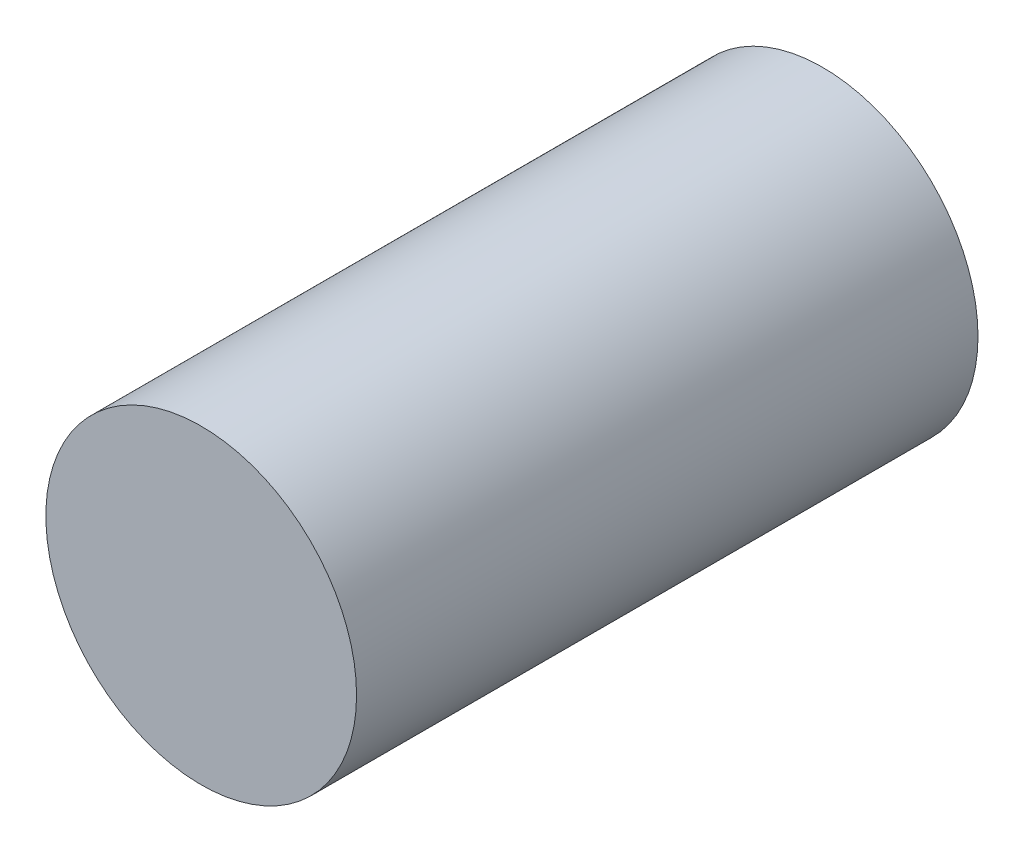
SolidWorks part; units mm, degrees
ref_plane "Front Plane" through (0, 0, 0) normal (0, 0, 1) x (1, 0, 0)
ref_plane "Top Plane" through (0, 0, 0) normal (0, 1, 0) x (1, 0, 0)
ref_plane "Right Plane" through (0, 0, 0) normal (1, 0, 0) x (0, 0, -1)
sketch "Sketch1" plane through (0, 0, 0) normal (0, 0, 1) x (1, 0, 0)
  circle A0 centre (0, 0) radius 25
  dimension "D1" = 50
extrude "Boss-Extrude1" add sketch "Sketch1" along normal blind 100
